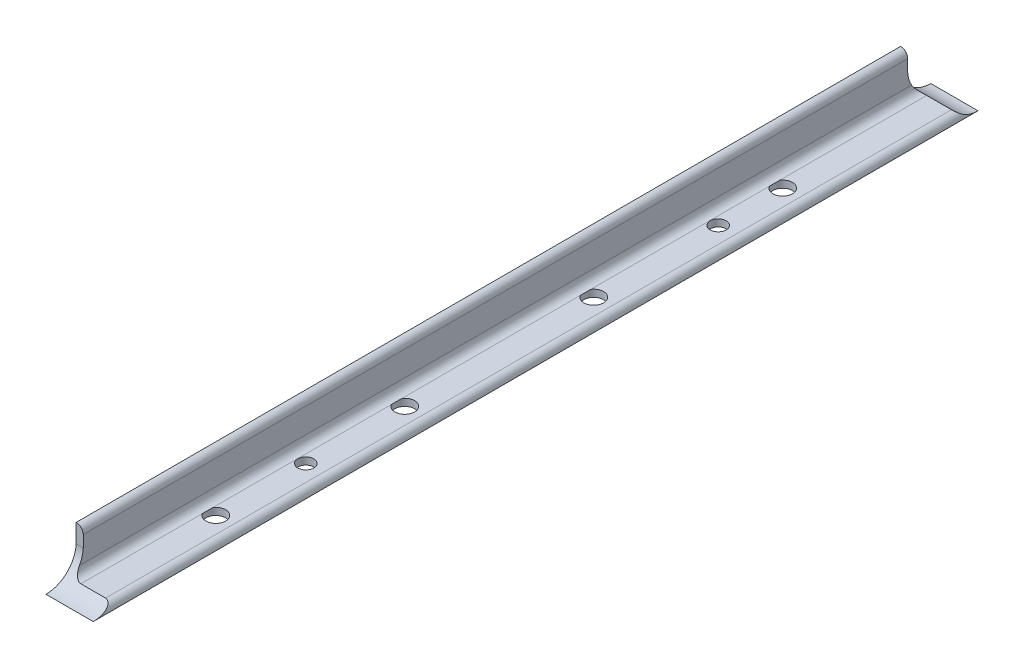
SolidWorks part; units mm, degrees
material "AISI 1010 Barra de acero laminada en caliente"
ref_plane "Alzado" through (0, 0, 0) normal (0, 0, 1) x (1, 0, 0)
ref_plane "Planta" through (0, 0, 0) normal (0, 1, 0) x (1, 0, 0)
ref_plane "Vista lateral" through (0, 0, 0) normal (1, 0, 0) x (0, 0, -1)
sketch "Croquis1" plane through (0, 0, 0) normal (0, 1, 0) x (1, 0, 0)
  line L0 (0, 193.229) -> (0, -181.371)
  dimension "D1" = 374.6
other "Miembro estructural1"
ref_plane "Plano1" through (0, 0, -193.229) normal (0, 0, 1) x (1, 0, 0)
sketch "Sketch1" plane through (0, 0, -193.229) normal (0, 0, 1) x (1, 0, 0)
  line L0 (0, 0) -> (0, 20)
  line L1 (0, 10) -> (3, 10) construction
  line L2 (3, 17) -> (3, 6.5)
  line L3 (6.5, 3) -> (17, 3)
  line L4 (10, 3) -> (10, 0) construction
  line L5 (20, 0) -> (0, 0)
  arc A0 (20, 0) -> (17, 3) centre (17, 0) ccw
  arc A1 (0, 20) -> (3, 17) centre (0, 17) cw
  arc A2 (6.5, 3) -> (3, 6.5) centre (6.5, 6.5) cw
  point P10 (10, 0)
  point P14 (0, 10)
  point P15 (3, 10)
  point P16 (10, 3)
  point P17 (3, 20)
  point P18 (20, 3)
  point P21 (0, 0)
  dimension "D2" = 3
  dimension "D3" = 20
  dimension "Radius_1" = 3.5
  dimension "D1" = 3
sketch "Croquis2" plane through (0, 0, 0) normal (1, 0, 0) x (0, 1, 0)
  line L0 (0, -193.229) -> (0, -196.9752)
  line L1 (0, -196.9752) -> (22.852, -196.9752)
  line L2 (22.852, -196.9752) -> (22.852, -180.4472)
  line L4 (22.852, -180.4472) -> (12.1191, -180.4472)
  line L5 (0, -5.929) -> (20, -5.929) construction
  line L7 (0, 181.371) -> (0, -193.229) construction
  line L8 (20, 181.371) -> (20, -193.229) construction
  line L9 (22.852, 168.5891) -> (12.1191, 168.5891)
  line L10 (22.852, 185.1172) -> (22.852, 168.5891)
  line L11 (0, 185.1172) -> (22.852, 185.1172)
  line L12 (0, 181.371) -> (0, 185.1172)
  arc A0 (0, -193.229) -> (12.1191, -180.4472) centre (12.8, -193.229) cw
  arc A1 (0, 181.371) -> (12.1191, 168.5891) centre (12.8, 181.371) ccw
  line M18 (0, 181.371) -> (20, 181.371)
  line M19 (20, 181.371) -> (20, -193.229)
  dimension "D1" = 12.8
extrude "Cortar-Extruir2" cut sketch "Croquis2" along normal through all contours A1 L9 M18 M19 | L4 A0 L0 L1 L2
hole_wizard "Taladro de margen para 1/41" positions "Croquis5" profile "Croquis3" hole size "1/4" standard "Ansi Inch" end condition through all
sketch "Croquis5" plane through (0, 0, 0) normal (0, -1, 0) x (-1, 0, 0)
  line L0 (-10, -181.371) -> (-10, 193.229) construction
  line L1 (0, -181.371) -> (-20, -181.371) construction
  line L2 (0, 193.229) -> (-20, 193.229) construction
  point P0 (-10, -81.371)
  point P2 (-10, 93.229)
  dimension "D1" = 100
  dimension "D2" = 100
sketch "Croquis3" plane through (10, 0, 81.371) normal (1, 0, 0) x (0, 0, -1)
  line L0 (0, 0) -> (0, 20)
  line L1 (0, 20) -> (3.3782, 20)
  line L2 (3.3782, 20) -> (3.3782, 0)
  line L5 (3.3782, 0) -> (0, 0)
  line L11 (0, -6.35) -> (0, 107.95) construction
  dimension "Diámetro de taladro hasta el siguiente" = 6.7564
  dimension "Profundidad de taladro hasta el siguiente" = 20
sketch "Sketch2" plane through (0, 0, 0) normal (0, -1, 0) x (1, 0, 0)
  line L2 (-0.215, -217.829) -> (20.215, -217.829) construction
  line L4 (10, -193.229) -> (10, -180.911) construction
  line L8 (-0.215, -230.529) -> (20.215, -230.529)
  line L9 (20.215, -230.529) -> (20.215, 169.471)
  line L11 (-0.215, 169.471) -> (-0.215, -230.529)
  line L12 (-0.215, -193.229) -> (20.215, -193.229) construction
  line L13 (0, -193.229) -> (20, -193.229)
  line L14 (20, -193.229) -> (20, 181.371)
  line L15 (20, 181.371) -> (0, 181.371)
  line L16 (0, 181.371) -> (0, -193.229)
  line L17 (22.3, 169.471) -> (-2.3, 169.471)
  line L18 (22.3, -180.529) -> (22.3, 169.471)
  line L19 (-2.3, -180.529) -> (22.3, -180.529)
  line L20 (-2.3, 169.471) -> (-2.3, -180.529)
  line L21 (10, -230.529) -> (10, -180.529) construction
  line L22 (20.215, -198.629) -> (-0.215, -198.629) construction
  line L23 (0, -193.229) -> (20, -193.229) construction
  line L24 (20, -193.229) -> (20, 181.371) construction
  line L25 (20, 181.371) -> (0, 181.371) construction
  line L26 (0, 181.371) -> (0, -193.229) construction
  circle A1 centre (10, -120.529) radius 4.1672
  circle A2 centre (10, -40.529) radius 4.1672
  circle A3 centre (10, 39.471) radius 4.1672
  circle A4 centre (10, 119.471) radius 4.1672
  arc A105 (17, 119.471) -> (3, 119.471) centre (10, 119.471) ccw construction
  arc A106 (17, 119.471) -> (3, 119.471) centre (10, 119.471) ccw
  arc A107 (17, 39.471) -> (3, 39.471) centre (10, 39.471) ccw construction
  arc A108 (17, 39.471) -> (3, 39.471) centre (10, 39.471) ccw
  arc A109 (17, -40.529) -> (3, -40.529) centre (10, -40.529) ccw construction
  arc A110 (17, -40.529) -> (3, -40.529) centre (10, -40.529) ccw
  arc A111 (17, -120.529) -> (3, -120.529) centre (10, -120.529) ccw construction
  arc A113 (17, -200.529) -> (3, -200.529) centre (10, -200.529) ccw
  arc A114 (17, -200.529) -> (3, -200.529) centre (10, -200.529) ccw
  arc A115 (3, -200.529) -> (17, -200.529) centre (10, -200.529) ccw
  arc A116 (3, -200.529) -> (17, -200.529) centre (10, -200.529) ccw
  arc A117 (3, -120.529) -> (17, -120.529) centre (10, -120.529) ccw construction
  arc A120 (3, -40.529) -> (17, -40.529) centre (10, -40.529) ccw construction
  arc A121 (3, 39.471) -> (17, 39.471) centre (10, 39.471) ccw construction
  arc A122 (3, 39.471) -> (17, 39.471) centre (10, 39.471) ccw
  arc A123 (3, 119.471) -> (17, 119.471) centre (10, 119.471) ccw construction
  arc A124 (3, 119.471) -> (17, 119.471) centre (10, 119.471) ccw
  dimension "D2" = 60
  dimension "D6" = 8.3344
  dimension "D7" = 8.3344
  dimension "D8" = 8.3344
  dimension "D9" = 8.3344
  dimension "D3" = 80
  dimension "D4" = 80
  dimension "D5" = 80
  dimension "D1" = 0
extrude "Cut-Extrude2" cut sketch "Sketch2" against normal up to surface (3 mm away) contours A2 | A3 | A4 | A1 up to face at (10, 3, 77.9928)
